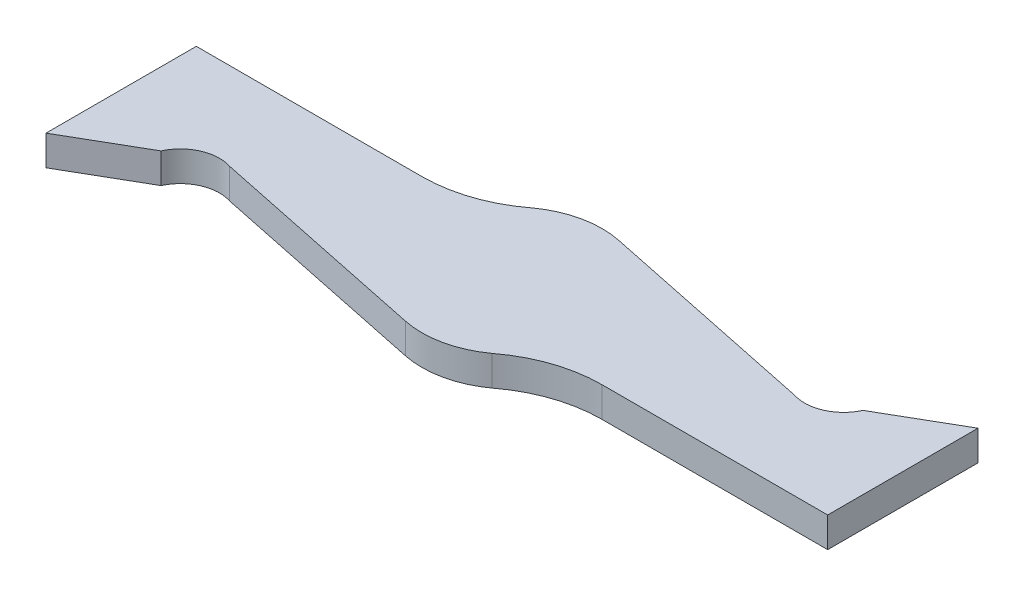
SolidWorks part; units mm, degrees
material "AR 500"
ref_plane "Front Plane" through (0, 0, 0) normal (0, 0, 1) x (1, 0, 0)
ref_plane "Top Plane" through (0, 0, 0) normal (0, 1, 0) x (1, 0, 0)
ref_plane "Right Plane" through (0, 0, 0) normal (1, 0, 0) x (0, 0, -1)
sketch "Sketch1" plane through (0, 0, 0) normal (0, 1, 0) x (1, 0, 0)
  line L0 (-152.4, 19.05) -> (-57.1576, 19.05)
  line L1 (-152.4, 50.8) -> (152.4, 50.8)
  line L2 (-152.4, 50.8) -> (-152.4, -50.8)
  line L3 (-152.4, -50.8) -> (152.4, -50.8)
  line L4 (152.4, 50.8) -> (152.4, -50.8)
  line L5 (-152.4, 50.8) -> (152.4, -50.8) construction
  line L6 (-152.4, -50.8) -> (152.4, 50.8) construction
  line L7 (-33.0032, 19.05) -> (32.9879, 19.05) construction
  line L8 (-33.0032, 19.05) -> (-33.0032, -19.05) construction
  line L9 (-33.0032, -19.05) -> (32.9879, -19.05) construction
  line L10 (32.9879, 19.05) -> (32.9879, -19.05) construction
  line L11 (-33.0032, 19.05) -> (32.9879, -19.05) construction
  line L12 (-33.0032, -19.05) -> (32.9879, 19.05) construction
  line L13 (-152.4, 19.05) -> (-152.4, -44.45)
  line L14 (-152.4, -44.45) -> (-121.6041, -26.67)
  line L15 (-121.6041, -26.67) -> (-101.5655, -17.7895) construction
  line L16 (152.4, -19.05) -> (57.15, -19.05)
  line L17 (152.4, -19.05) -> (152.4, 44.45)
  line L18 (152.4, 44.45) -> (121.6041, 26.67)
  line L19 (101.5655, 17.7895) -> (7.7506, 37.3017)
  line L20 (121.6041, 26.67) -> (101.5655, 17.7895) construction
  line L21 (-101.5655, -17.7895) -> (-7.7671, -37.3015)
  circle A0 centre (-0.0076, 0) radius 38.1
  arc A1 (-121.6041, -26.67) -> (-101.5655, -17.7895) centre (-106.5818, -33.519) cw
  arc A2 (121.6041, 26.67) -> (101.5655, 17.7895) centre (106.5818, 33.519) cw
  arc A3 (57.15, -19.05) -> (22.4174, -30.8014) centre (57.15, -76.2536) ccw
  arc A4 (-57.1576, 19.05) -> (-22.2931, 30.9025) centre (-57.1576, 76.2536) ccw
  point P1 (0, 0)
  dimension "D3" = 76.2
  dimension "D12" = 16.51
  dimension "D13" = 16.51
  dimension "D14" = 57.2036
  dimension "D18" = 57.2036
  dimension "D1" = 101.6
  dimension "D2" = 304.8
  dimension "D4" = 0.0076
  dimension "D5" = 38.1
  dimension "D6" = 63.5
  dimension "D7" = 60
  dimension "D8" = 35.56
  dimension "D9" = 63.5
  dimension "D10" = 60
  dimension "D11" = 35.56
  dimension "D15" = 21.9182
  dimension "D16" = 21.9182
  dimension "D17" = 13.4426
  dimension "D19" = 95.2424
extrude "Boss-Extrude1" add sketch "Sketch1" along normal blind 12.7
